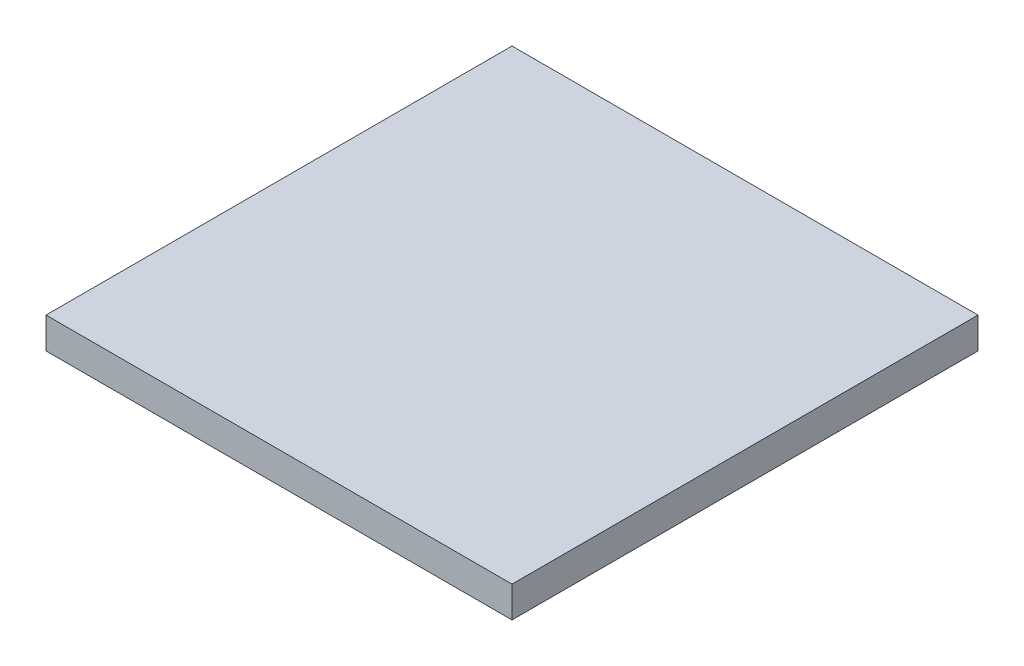
SolidWorks part; units mm, degrees
ref_plane "Front Plane" through (0, 0, 0) normal (0, 0, 1) x (1, 0, 0)
ref_plane "Top Plane" through (0, 0, 0) normal (0, 1, 0) x (1, 0, 0)
ref_plane "Right Plane" through (0, 0, 0) normal (1, 0, 0) x (0, 0, -1)
sketch "Sketch1" plane through (0, 0, 0) normal (0, 1, 0) x (1, 0, 0)
  line L1 (-150, -150) -> (150, -150)
  line L2 (-150, -150) -> (-150, 150)
  line L3 (-150, 150) -> (150, 150)
  line L4 (150, -150) -> (150, 150)
  line L5 (-150, -150) -> (150, 150) construction
  line L6 (-150, 150) -> (150, -150) construction
  point P0 (0, 0)
  dimension "D1" = 300
extrude "Boss-Extrude1" add sketch "Sketch1" along normal blind 20
sketch "Sketch2" plane through (0, 0, 0) normal (0, 1, 0) x (1, 0, 0)
  circle A0 centre (0, 0) radius 5
  dimension "D1" = 10
